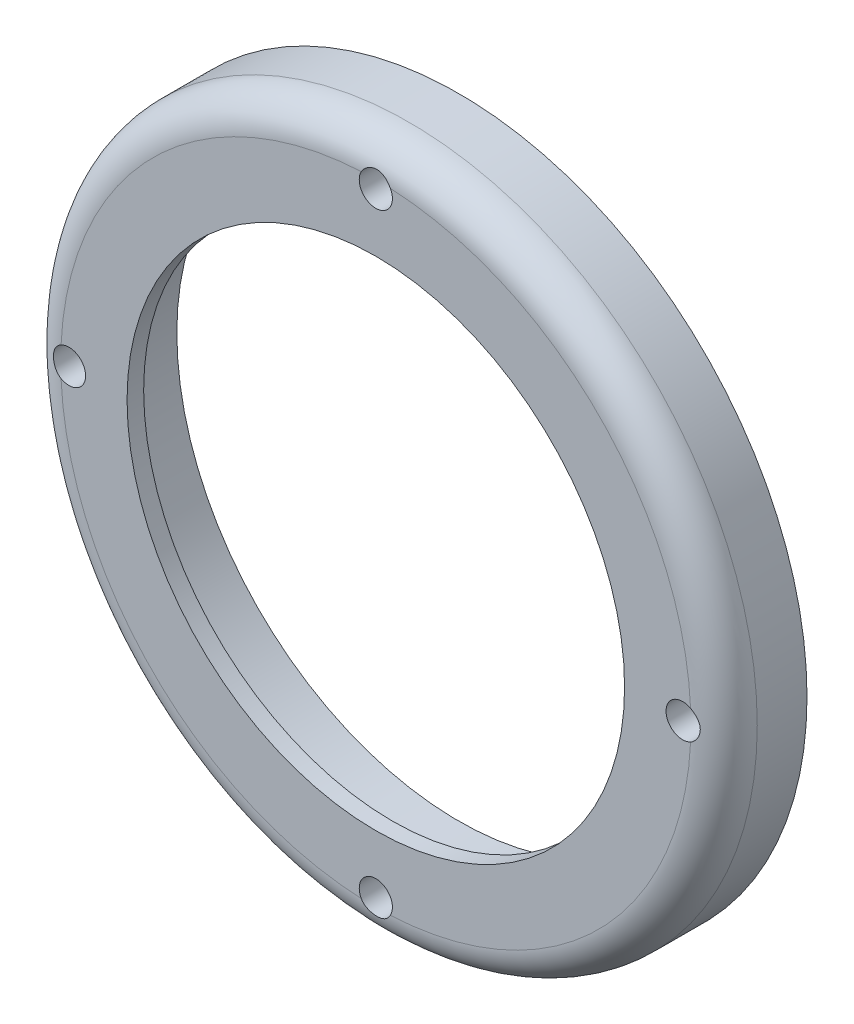
SolidWorks part; units mm, degrees
ref_plane "Front Plane" through (0, 0, 0) normal (0, 0, 1) x (1, 0, 0)
ref_plane "Top Plane" through (0, 0, 0) normal (0, 1, 0) x (1, 0, 0)
ref_plane "Right Plane" through (0, 0, 0) normal (1, 0, 0) x (0, 0, -1)
sketch "Sketch1" plane through (0, 0, 0) normal (0, 0, 1) x (1, 0, 0)
  circle A0 centre (0, 0) radius 52.5
  dimension "D1" = 105
extrude "Boss-Extrude1" add sketch "Sketch1" along normal blind 20
sketch "Sketch2" plane through (0, 0, 0) normal (0, 0, -1) x (-1, 0, 0)
  circle A0 centre (0, 0) radius 40
  circle A1 centre (0, 0) radius 42.5
  dimension "D1" = 85
  dimension "D2" = 80
extrude "Cut-Extrude1" cut sketch "Sketch2" against normal blind 10
sketch "Sketch4" plane through (0, 0, 0) normal (0, 0, -1) x (-1, 0, 0)
  circle A0 centre (0, 0) radius 40
  dimension "D1" = 80
extrude "Cut-Extrude3" cut sketch "Sketch4" against normal blind 10
sketch "Sketch8" plane through (0, 0, 20) normal (0, 0, 1) x (1, 0, 0)
  circle A0 centre (0, 0) radius 55
  dimension "D1" = 110
extrude "Cut-Extrude4" cut sketch "Sketch8" against normal blind 7.5
sketch "Sketch9" plane through (0, 0, 10) normal (0, 0, -1) x (-1, 0, 0)
  circle A0 centre (0, 0) radius 37.5
  dimension "D1" = 75
extrude "Cut-Extrude5" cut sketch "Sketch9" against normal blind 2.5 contours A0
fillet "Fillet1" radius 5 1 edges at (52.5, 0, 12.5)
sketch "Sketch10" plane through (0, 0, 12.5) normal (0, 0, 1) x (1, 0, 0)
  circle A0 centre (0, 46.25) radius 2.5
  circle A1 centre (46.25, 0) radius 2.5
  circle A2 centre (0, -46.25) radius 2.5
  circle A3 centre (-46.25, 0) radius 2.5
  dimension "D2" = 5
  dimension "D6" = 5
  dimension "D7" = 5
  dimension "D8" = 5
  dimension "D1" = 46.25
  dimension "D3" = 46.25
  dimension "D4" = 46.25
  dimension "D5" = 46.25
extrude "Cut-Extrude6" cut sketch "Sketch10" against normal blind 5
sketch "Sketch11" plane through (0, 0, 7.5) normal (0, 0, 1) x (1, 0, 0)
  circle A3 centre (0, 46.25) radius 1.5
  dimension "D1" = 3
extrude "Cut-Extrude7" cut sketch "Sketch11" against normal blind 7.5
sketch "Sketch13" plane through (0, 0, 7.5) normal (0, 0, 1) x (1, 0, 0)
  circle A0 centre (0, -46.25) radius 1.5
  dimension "D1" = 3
extrude "Cut-Extrude9" cut sketch "Sketch13" against normal blind 7.5
sketch "Sketch14" plane through (0, 0, 7.5) normal (0, 0, 1) x (1, 0, 0)
  circle A0 centre (-46.25, 0) radius 1.5
  dimension "D1" = 3
extrude "Cut-Extrude10" cut sketch "Sketch14" against normal blind 7.5
sketch "Sketch15" plane through (0, 0, 7.5) normal (0, 0, 1) x (1, 0, 0)
  circle A0 centre (46.25, 0) radius 1.5
  dimension "D1" = 3
extrude "Cut-Extrude11" cut sketch "Sketch15" against normal blind 7.5
